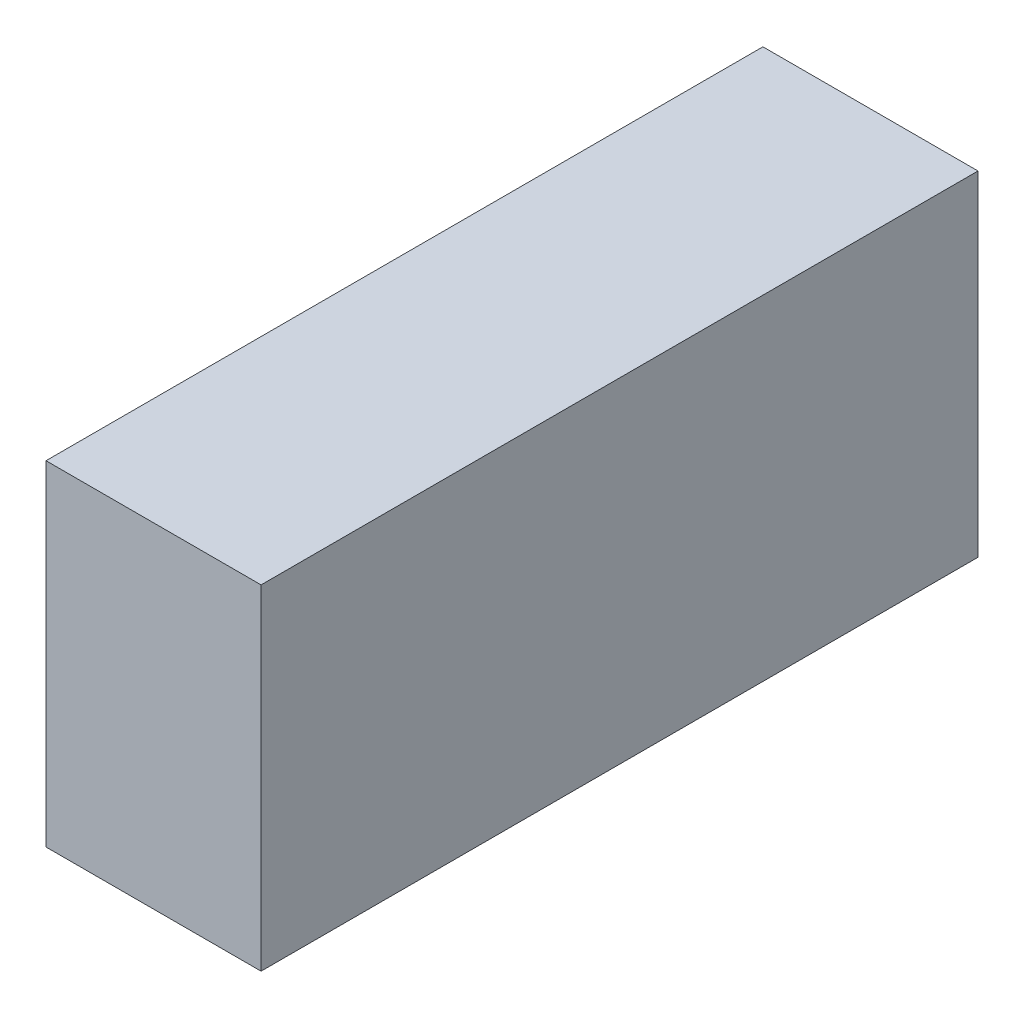
SolidWorks part; units mm, degrees
material "Titanium"
ref_plane "Front Plane" through (0, 0, 0) normal (0, 0, 1) x (1, 0, 0)
ref_plane "Top Plane" through (0, 0, 0) normal (0, 1, 0) x (1, 0, 0)
ref_plane "Right Plane" through (0, 0, 0) normal (1, 0, 0) x (0, 0, -1)
sketch "Sketch1" plane through (0, 0, 0) normal (0, 0, 1) x (1, 0, 0)
  line L1 (-0.9, -1.4) -> (0.9, -1.4)
  line L2 (-0.9, -1.4) -> (-0.9, 1.4)
  line L3 (-0.9, 1.4) -> (0.9, 1.4)
  line L4 (0.9, -1.4) -> (0.9, 1.4)
  line L5 (-0.9, -1.4) -> (0.9, 1.4) construction
  line L6 (-0.9, 1.4) -> (0.9, -1.4) construction
  point P0 (0, 0)
  dimension "D1" = 2.8
  dimension "D2" = 1.8
extrude "Boss-Extrude1" add sketch "Sketch1" along normal blind 6
